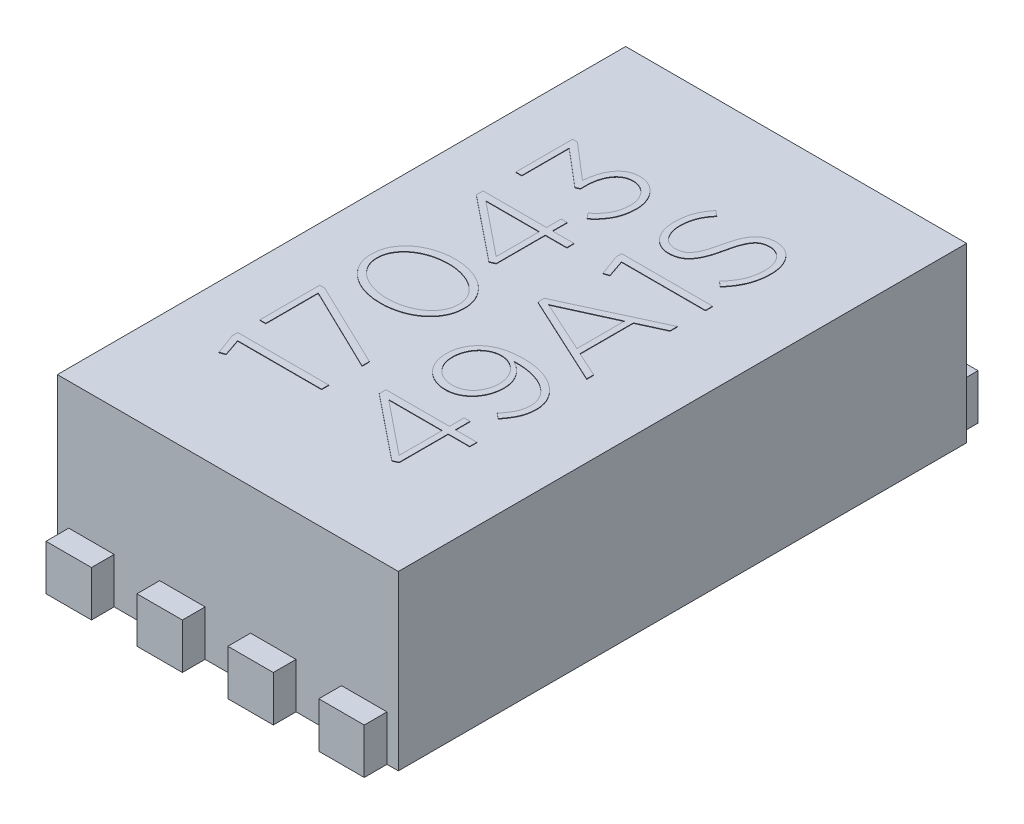
SolidWorks part; units mm, degrees
ref_plane "Front Plane" through (0, 0, 0) normal (0, 0, 1) x (1, 0, 0)
ref_plane "Top Plane" through (0, 0, 0) normal (0, 1, 0) x (1, 0, 0)
ref_plane "Right Plane" through (0, 0, 0) normal (1, 0, 0) x (0, 0, -1)
sketch "Sketch1" plane through (0, 0, 0) normal (0, 1, 0) x (1, 0, 0)
  line L1 (-0.9525, 1.5875) -> (0.9525, 1.5875)
  line L2 (-0.9525, 1.5875) -> (-0.9525, -1.5875)
  line L3 (-0.9525, -1.5875) -> (0.9525, -1.5875)
  line L4 (0.9525, 1.5875) -> (0.9525, -1.5875)
  line L5 (-0.9525, 1.5875) -> (0.9525, -1.5875) construction
  line L6 (-0.9525, -1.5875) -> (0.9525, 1.5875) construction
  point P0 (0, 0)
  dimension "D1" = 1.905
  dimension "D2" = 3.175
extrude "Boss-Extrude1" add sketch "Sketch1" along normal blind 0.9652
sketch "Sketch2" plane through (0, 0, 1.5875) normal (0, 0, 1) x (1, 0, 0)
  line L0 (-0.635, 0) -> (-0.381, 0) construction
  line L1 (-0.635, 0) -> (-0.889, 0)
  line L2 (-0.635, 0) -> (-0.635, 0.254)
  line L3 (-0.635, 0.254) -> (-0.889, 0.254)
  line L4 (-0.889, 0) -> (-0.889, 0.254)
  line L5 (-0.381, 0) -> (-0.127, 0)
  line L6 (-0.381, 0) -> (-0.381, 0.254)
  line L7 (-0.381, 0.254) -> (-0.127, 0.254)
  line L8 (-0.127, 0) -> (-0.127, 0.254)
  line L9 (0.127, 0) -> (0.381, 0)
  line L10 (0.127, 0) -> (0.127, 0.254)
  line L11 (0.127, 0.254) -> (0.381, 0.254)
  line L12 (0.381, 0) -> (0.381, 0.254)
  line L13 (0.635, 0) -> (0.889, 0)
  line L14 (0.635, 0) -> (0.635, 0.254)
  line L15 (0.635, 0.254) -> (0.889, 0.254)
  line L16 (0.889, 0) -> (0.889, 0.254)
  line L17 (-0.127, 0) -> (0.127, 0) construction
  line L18 (0.381, 0) -> (0.635, 0) construction
  line L19 (-0.9525, 0) -> (0.9525, 0) construction
  point P18 (0, 0)
  point P19 (0, 0)
  dimension "D1" = 0.254
  dimension "D2" = 0.254
  dimension "D3" = 0.254
extrude "Boss-Extrude2" add sketch "Sketch2" along normal blind 0.127
mirror "Mirror1" about plane through (0, 0, 0) normal (0, 0, 1) of "Boss-Extrude2"
sketch "Sketch3" plane through (0, 0.9652, 0) normal (0, 1, 0) x (1, 0, 0)
  line L0 (-0.1415, -1.2607) -> (-0.1415, 1.2607) construction
  line L1 (0.5493, -1.2607) -> (0.5493, 1.2607) construction
  text T0 "17043" font "Gotham Light" height 0.508
  text T1 "49A1S" font "Gotham Light" height 0.508
  point P6 (0.5493, 0)
  point P7 (-0.1415, 0)
extrude "Boss-Extrude3" add sketch "Sketch3" along normal blind 0.0025
